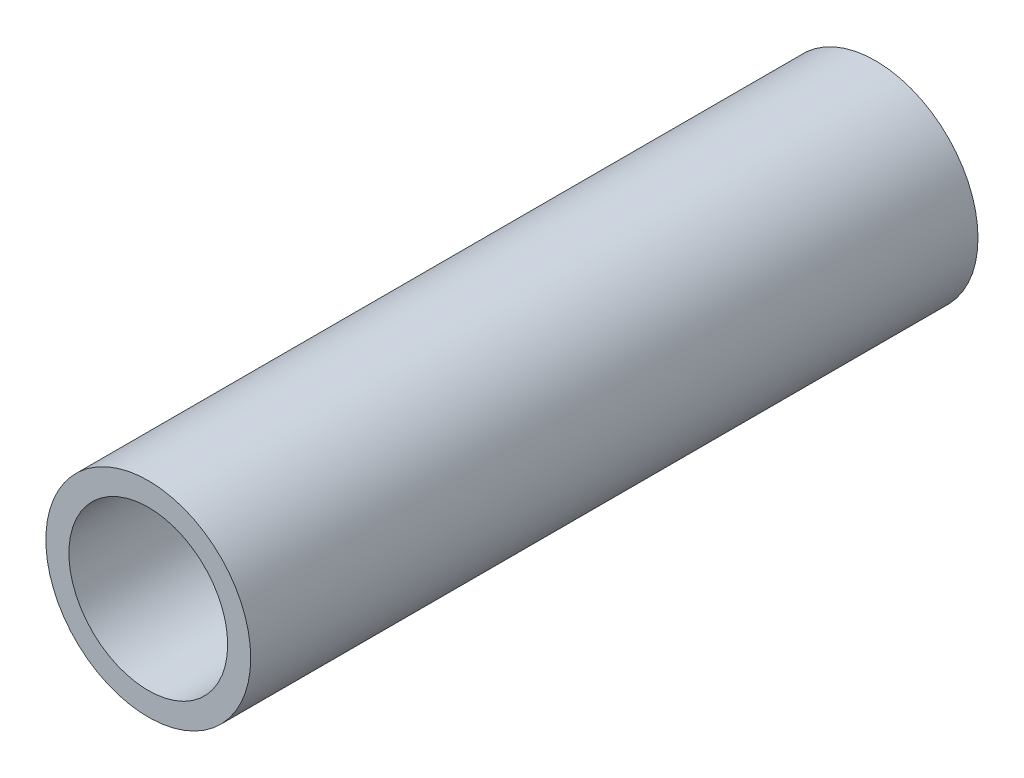
SolidWorks part; units mm, degrees
ref_plane "Спереди" through (0, 0, 0) normal (0, 0, 1) x (1, 0, 0)
ref_plane "Сверху" through (0, 0, 0) normal (0, 1, 0) x (1, 0, 0)
ref_plane "Справа" through (0, 0, 0) normal (1, 0, 0) x (0, 0, -1)
sketch "Эскиз1" plane through (0, 0, 0) normal (0, 0, 1) x (1, 0, 0)
  circle A0 centre (0, 0) radius 1
  circle A1 centre (0, 0) radius 0.775
extrude "Бобышка-Вытянуть1" add sketch "Эскиз1" along normal blind 7.1
